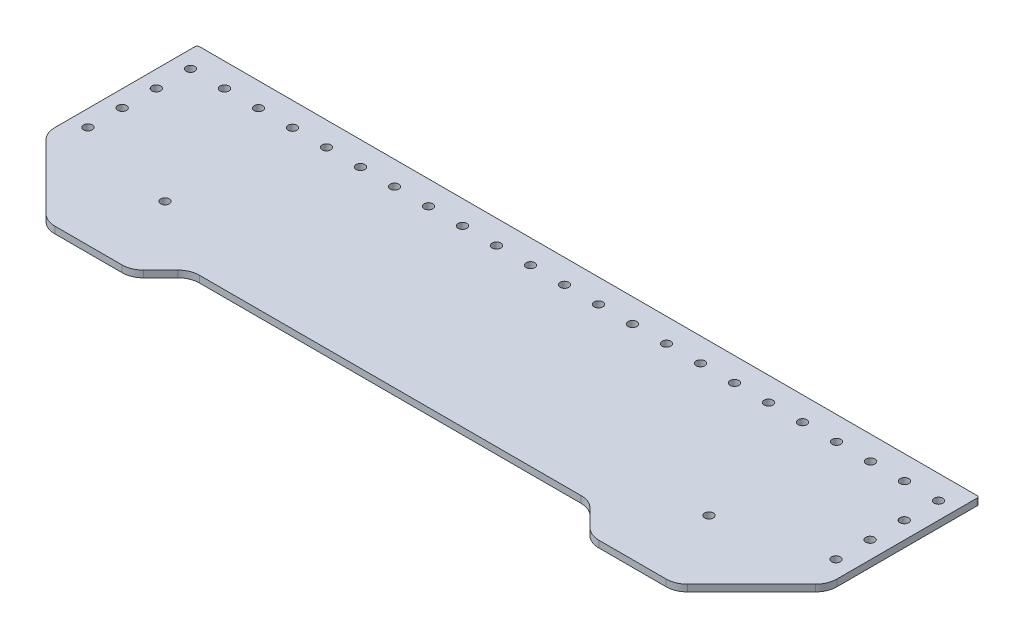
SolidWorks part; units mm, degrees
ref_plane "Front Plane" through (0, 0, 0) normal (0, 0, 1) x (1, 0, 0)
ref_plane "Top Plane" through (0, 0, 0) normal (0, 1, 0) x (1, 0, 0)
ref_plane "Right Plane" through (0, 0, 0) normal (1, 0, 0) x (0, 0, -1)
sketch "Sketch3" plane through (0, 0, 0) normal (0, 1, 0) x (1, 0, 0)
  line L0 (0, 0) -> (50000, 0) construction
  line L1 (184, -59.5875) -> (-184, -59.5875) construction
  line L2 (184, -59.5875) -> (184, 59.5875) construction
  line L3 (184, 59.5875) -> (-184, 59.5875) construction
  line L4 (-184, -59.5875) -> (-184, 59.5875) construction
  line L5 (184, -59.5875) -> (-184, 59.5875) construction
  line L6 (184, 59.5875) -> (-184, -59.5875) construction
  line L7 (0, 0) -> (0, -50000) construction
  line L8 (-141.9903, -11.5875) -> (49858.0097, -11.5875) construction
  line L9 (-130.2701, 7.3771) -> (-33.4655, 18.9646) construction
  line L10 (-128, -11.5875) -> (-31.1955, 0) construction
  line L11 (-125.7299, -30.5521) -> (-28.9254, -18.9646) construction
  line L12 (-49.1677, -33.5875) -> (49950.8323, -33.5875) construction
  line L13 (-47.419, -47.5875) -> (-50047.419, -47.5875) construction
  line L14 (-184, -11.5875) -> (-148, -47.5875)
  line L15 (-128, -11.5875) -> (-128, -50011.5875) construction
  line L16 (-148, -47.5875) -> (-108, -47.5875)
  line L17 (-94, -33.5875) -> (-108, -47.5875)
  line L18 (-94, -33.5875) -> (94, -33.5875)
  line L19 (-184, -11.5875) -> (-184, 59.5875)
  line L20 (-184, 59.5875) -> (184, 59.5875)
  line L21 (184, -11.5875) -> (184, 59.5875)
  line L22 (184, -11.5875) -> (148, -47.5875)
  line L23 (148, -47.5875) -> (108, -47.5875)
  line L24 (94, -33.5875) -> (108, -47.5875)
  line L26 (-15.1955, -16) -> (-47.1955, -16) construction
  line L27 (-15.1955, -16) -> (-15.1955, 16) construction
  line L28 (-15.1955, 16) -> (-47.1955, 16) construction
  line L29 (-47.1955, -16) -> (-47.1955, 16) construction
  line L30 (-15.1955, -16) -> (-47.1955, 16) construction
  line L31 (-15.1955, 16) -> (-47.1955, -16) construction
  line L32 (-9.1955, -22) -> (-53.1955, -22) construction
  line L33 (-9.1955, -22) -> (-9.1955, 22) construction
  line L34 (-9.1955, 22) -> (-53.1955, 22) construction
  line L35 (-53.1955, -22) -> (-53.1955, 22) construction
  line L36 (-9.1955, -22) -> (-53.1955, 22) construction
  line L37 (-9.1955, 22) -> (-53.1955, -22) construction
  circle A0 centre (-128, -11.5875) radius 48 construction
  circle A1 centre (-128, -11.5875) radius 19.1 construction
  circle A2 centre (-31.1955, 0) radius 19.1 construction
  arc A3 (-33.4655, 18.9646) -> (-28.9254, -18.9646) centre (-31.1955, 0) cw construction
  arc A4 (-130.2701, 7.3771) -> (-125.7299, -30.5521) centre (-128, -11.5875) ccw construction
  circle A5 centre (-128, -11.5875) radius 2.05
  circle A7 centre (128, -11.5875) radius 2.05
  circle A9 centre (-53.1955, 22) radius 2.05 construction
  circle A10 centre (-53.1955, -22) radius 2.05 construction
  circle A11 centre (53.1955, 22) radius 2.05 construction
  circle A12 centre (53.1955, -22) radius 2.05 construction
  circle A13 centre (-31.1955, 0) radius 17.5 construction
  circle A14 centre (31.1955, 0) radius 17.5 construction
  point P0 (0, 0)
  point P36 (0, 59.5875)
  point P40 (0, -33.5875)
  dimension "D4" = 96
  dimension "D6" = 38.2
  dimension "D12" = 4.1
  dimension "D15" = 35
  dimension "D1" = 368
  dimension "D2" = 119.175
  dimension "D3" = 48
  dimension "D5" = 56
  dimension "D8" = 26
  dimension "D9" = 12
  dimension "D10" = 45
  dimension "D11" = 45
  dimension "D13" = 32
  dimension "D14" = 44
extrude "Boss-Extrude2" add sketch "Sketch3" along normal blind 3.175
fillet "Fillet1" radius 10 8 edges at (184, 1.5875, 11.5875) (148, 1.5875, 47.5875) (108, 1.5875, 47.5875) (94, 1.5875, 33.5875) (-94, 1.5875, 33.5875) (-108, 1.5875, 47.5875) (-148, 1.5875, 47.5875) (-184, 1.5875, 11.5875)
fillet "Fillet2" radius 1 2 edges at (184, 1.5875, -59.5875) (-184, 1.5875, -59.5875)
sketch "Sketch5" plane through (0, 3.175, 0) normal (0, 1, 0) x (1, 0, 0)
  line L0 (0, 0) -> (0, -50000) construction
  circle A0 centre (-128, -11.5875) radius 48
  circle A1 centre (128, -11.5875) radius 48
  dimension "D1" = 96
sketch "Sketch6" plane through (0, 3.175, 0) normal (0, 1, 0) x (1, 0, 0)
  line L0 (0, 0) -> (0, -50000) construction
  line L1 (-160.014, 32.4127) -> (49839.986, 32.4127) construction
  line L2 (0, 0) -> (50000, 0) construction
  line L3 (21.2444, 56.4125) -> (50021.2444, 56.4125) construction
  line L4 (21.9898, 48.4125) -> (50021.9898, 48.4125) construction
  line L5 (183, 59.5875) -> (-183, 59.5875) construction
  line L6 (-176, 42.191) -> (-176, -49957.809) construction
  line L7 (-184, 58.5875) -> (-184, -7.4454) construction
  line L8 (-176, 48.4125) -> (-160, 48.4125) construction
  line L9 (-176, 48.4125) -> (-176.0869, 32.4127) construction
  circle A0 centre (-176, 48.4125) radius 2.05
  circle A1 centre (-160, 48.4125) radius 2.05
  circle A2 centre (-144, 48.4125) radius 2.05
  circle A3 centre (-128, 48.4125) radius 2.05
  circle A4 centre (-112, 48.4125) radius 2.05
  circle A5 centre (-96, 48.4125) radius 2.05
  circle A6 centre (-80, 48.4125) radius 2.05
  circle A7 centre (-64, 48.4125) radius 2.05
  circle A8 centre (-48, 48.4125) radius 2.05
  circle A9 centre (-32, 48.4125) radius 2.05
  circle A10 centre (-16, 48.4125) radius 2.05
  circle A11 centre (0, 48.4125) radius 2.05
  circle A12 centre (16, 48.4125) radius 2.05
  circle A13 centre (32, 48.4125) radius 2.05
  circle A14 centre (48, 48.4125) radius 2.05
  circle A15 centre (64, 48.4125) radius 2.05
  circle A16 centre (80, 48.4125) radius 2.05
  circle A17 centre (96, 48.4125) radius 2.05
  circle A18 centre (112, 48.4125) radius 2.05
  circle A19 centre (128, 48.4125) radius 2.05
  circle A20 centre (144, 48.4125) radius 2.05
  circle A21 centre (160, 48.4125) radius 2.05
  circle A22 centre (176, 48.4125) radius 2.05
  circle A23 centre (-160.0869, 32.4127) radius 2.05 construction
  circle A24 centre (-144.0869, 32.4127) radius 2.05 construction
  circle A25 centre (-128.0869, 32.4127) radius 2.05 construction
  circle A26 centre (-112.0869, 32.4127) radius 2.05 construction
  circle A27 centre (-96.0869, 32.4127) radius 2.05 construction
  circle A28 centre (-80.0869, 32.4127) radius 2.05 construction
  circle A29 centre (-64.0869, 32.4127) radius 2.05 construction
  circle A30 centre (-48.0869, 32.4127) radius 2.05 construction
  circle A31 centre (-32.0869, 32.4127) radius 2.05 construction
  circle A32 centre (-16.0869, 32.4127) radius 2.05 construction
  circle A33 centre (-0.0869, 32.4127) radius 2.05 construction
  circle A34 centre (15.9131, 32.4127) radius 2.05 construction
  circle A35 centre (31.9131, 32.4127) radius 2.05 construction
  circle A36 centre (47.9131, 32.4127) radius 2.05 construction
  circle A37 centre (63.9131, 32.4127) radius 2.05 construction
  circle A38 centre (79.9131, 32.4127) radius 2.05 construction
  circle A39 centre (95.9131, 32.4127) radius 2.05 construction
  circle A40 centre (111.9131, 32.4127) radius 2.05 construction
  circle A41 centre (127.9131, 32.4127) radius 2.05 construction
  circle A42 centre (143.9131, 32.4127) radius 2.05 construction
  circle A43 centre (159.9131, 32.4127) radius 2.05 construction
  circle A44 centre (175.9131, 32.4127) radius 2.05
  circle A45 centre (-160.1738, 16.413) radius 2.05 construction
  circle A46 centre (-144.1738, 16.413) radius 2.05 construction
  circle A47 centre (-128.1738, 16.413) radius 2.05 construction
  circle A48 centre (-112.1738, 16.413) radius 2.05 construction
  circle A49 centre (-96.1738, 16.413) radius 2.05 construction
  circle A50 centre (-80.1738, 16.413) radius 2.05 construction
  circle A51 centre (-64.1738, 16.413) radius 2.05 construction
  circle A52 centre (-48.1738, 16.413) radius 2.05 construction
  circle A53 centre (-32.1738, 16.413) radius 2.05 construction
  circle A54 centre (-16.1738, 16.413) radius 2.05 construction
  circle A55 centre (-0.1738, 16.413) radius 2.05 construction
  circle A56 centre (15.8262, 16.413) radius 2.05 construction
  circle A57 centre (31.8262, 16.413) radius 2.05 construction
  circle A58 centre (47.8262, 16.413) radius 2.05 construction
  circle A59 centre (63.8262, 16.413) radius 2.05 construction
  circle A60 centre (79.8262, 16.413) radius 2.05 construction
  circle A61 centre (95.8262, 16.413) radius 2.05 construction
  circle A62 centre (111.8262, 16.413) radius 2.05 construction
  circle A63 centre (127.8262, 16.413) radius 2.05 construction
  circle A64 centre (143.8262, 16.413) radius 2.05 construction
  circle A65 centre (159.8262, 16.413) radius 2.05 construction
  circle A66 centre (175.8262, 16.413) radius 2.05
  circle A67 centre (-160.2607, 0.4132) radius 2.05 construction
  circle A68 centre (-144.2607, 0.4132) radius 2.05 construction
  circle A69 centre (-128.2607, 0.4132) radius 2.05 construction
  circle A70 centre (-112.2607, 0.4132) radius 2.05 construction
  circle A71 centre (-96.2607, 0.4132) radius 2.05 construction
  circle A72 centre (-80.2607, 0.4132) radius 2.05 construction
  circle A73 centre (-64.2607, 0.4132) radius 2.05 construction
  circle A74 centre (-48.2607, 0.4132) radius 2.05 construction
  circle A75 centre (-32.2607, 0.4132) radius 2.05 construction
  circle A76 centre (-16.2607, 0.4132) radius 2.05 construction
  circle A77 centre (-0.2607, 0.4132) radius 2.05 construction
  circle A78 centre (15.7393, 0.4132) radius 2.05 construction
  circle A79 centre (31.7393, 0.4132) radius 2.05 construction
  circle A80 centre (47.7393, 0.4132) radius 2.05 construction
  circle A81 centre (63.7393, 0.4132) radius 2.05 construction
  circle A82 centre (79.7393, 0.4132) radius 2.05 construction
  circle A83 centre (95.7393, 0.4132) radius 2.05 construction
  circle A84 centre (111.7393, 0.4132) radius 2.05 construction
  circle A85 centre (127.7393, 0.4132) radius 2.05 construction
  circle A86 centre (143.7393, 0.4132) radius 2.05 construction
  circle A87 centre (159.7393, 0.4132) radius 2.05 construction
  circle A88 centre (175.7393, 0.4132) radius 2.05
  circle A89 centre (-160.3476, -15.5866) radius 2.05 construction
  circle A90 centre (-144.3476, -15.5866) radius 2.05 construction
  circle A91 centre (-128.3476, -15.5866) radius 2.05 construction
  circle A92 centre (-112.3476, -15.5866) radius 2.05 construction
  circle A93 centre (-96.3476, -15.5866) radius 2.05 construction
  circle A94 centre (-80.3476, -15.5866) radius 2.05 construction
  circle A95 centre (-64.3476, -15.5866) radius 2.05 construction
  circle A96 centre (-48.3476, -15.5866) radius 2.05 construction
  circle A97 centre (-32.3476, -15.5866) radius 2.05 construction
  circle A98 centre (-16.3476, -15.5866) radius 2.05 construction
  circle A99 centre (-0.3476, -15.5866) radius 2.05 construction
  circle A100 centre (15.6524, -15.5866) radius 2.05 construction
  circle A101 centre (31.6524, -15.5866) radius 2.05 construction
  circle A102 centre (47.6524, -15.5866) radius 2.05 construction
  circle A103 centre (63.6524, -15.5866) radius 2.05 construction
  circle A104 centre (79.6524, -15.5866) radius 2.05 construction
  circle A105 centre (95.6524, -15.5866) radius 2.05 construction
  circle A106 centre (111.6524, -15.5866) radius 2.05 construction
  circle A107 centre (127.6524, -15.5866) radius 2.05 construction
  circle A108 centre (143.6524, -15.5866) radius 2.05 construction
  circle A109 centre (159.6524, -15.5866) radius 2.05 construction
  circle A110 centre (175.6524, -15.5866) radius 2.05 construction
  circle A111 centre (-160.4345, -31.5863) radius 2.05 construction
  circle A112 centre (-144.4345, -31.5863) radius 2.05 construction
  circle A113 centre (-128.4345, -31.5863) radius 2.05 construction
  circle A114 centre (-112.4345, -31.5863) radius 2.05 construction
  circle A115 centre (-96.4345, -31.5863) radius 2.05 construction
  circle A116 centre (-80.4345, -31.5863) radius 2.05 construction
  circle A117 centre (-64.4345, -31.5863) radius 2.05 construction
  circle A118 centre (-48.4345, -31.5863) radius 2.05 construction
  circle A119 centre (-32.4345, -31.5863) radius 2.05 construction
  circle A120 centre (-16.4345, -31.5863) radius 2.05 construction
  circle A121 centre (-0.4345, -31.5863) radius 2.05 construction
  circle A122 centre (15.5655, -31.5863) radius 2.05 construction
  circle A123 centre (31.5655, -31.5863) radius 2.05 construction
  circle A124 centre (47.5655, -31.5863) radius 2.05 construction
  circle A125 centre (63.5655, -31.5863) radius 2.05 construction
  circle A126 centre (79.5655, -31.5863) radius 2.05 construction
  circle A127 centre (95.5655, -31.5863) radius 2.05 construction
  circle A128 centre (111.5655, -31.5863) radius 2.05 construction
  circle A129 centre (127.5655, -31.5863) radius 2.05 construction
  circle A130 centre (143.5655, -31.5863) radius 2.05 construction
  circle A131 centre (159.5655, -31.5863) radius 2.05 construction
  circle A132 centre (175.5655, -31.5863) radius 2.05 construction
  circle A133 centre (-160.5214, -47.5861) radius 2.05 construction
  circle A134 centre (-144.5214, -47.5861) radius 2.05 construction
  circle A135 centre (-128.5214, -47.5861) radius 2.05 construction
  circle A136 centre (-112.5214, -47.5861) radius 2.05 construction
  circle A137 centre (-96.5214, -47.5861) radius 2.05 construction
  circle A138 centre (-80.5214, -47.5861) radius 2.05 construction
  circle A139 centre (-64.5214, -47.5861) radius 2.05 construction
  circle A140 centre (-48.5214, -47.5861) radius 2.05 construction
  circle A141 centre (-32.5214, -47.5861) radius 2.05 construction
  circle A142 centre (-16.5214, -47.5861) radius 2.05 construction
  circle A143 centre (-0.5214, -47.5861) radius 2.05 construction
  circle A144 centre (15.4786, -47.5861) radius 2.05 construction
  circle A145 centre (31.4786, -47.5861) radius 2.05 construction
  circle A146 centre (47.4786, -47.5861) radius 2.05 construction
  circle A147 centre (63.4786, -47.5861) radius 2.05 construction
  circle A148 centre (79.4786, -47.5861) radius 2.05 construction
  circle A149 centre (95.4786, -47.5861) radius 2.05 construction
  circle A150 centre (111.4786, -47.5861) radius 2.05 construction
  circle A151 centre (127.4786, -47.5861) radius 2.05 construction
  circle A152 centre (143.4786, -47.5861) radius 2.05 construction
  circle A153 centre (159.4786, -47.5861) radius 2.05 construction
  circle A154 centre (175.4786, -47.5861) radius 2.05 construction
  circle A155 centre (-176.0869, 32.4127) radius 2.05
  circle A156 centre (-176.1738, 16.413) radius 2.05
  circle A157 centre (-176.2607, 0.4132) radius 2.05
  circle A158 centre (-176.3476, -15.5866) radius 2.05 construction
  circle A159 centre (-176.4345, -31.5863) radius 2.05 construction
  circle A160 centre (-176.5214, -47.5861) radius 2.05 construction
  circle A161 centre (-25.0869, 32.4127) radius 2.05 construction
  circle A162 centre (25.0869, 32.4127) radius 2.05 construction
  circle A163 centre (109.9131, 32.4127) radius 2.05 construction
  circle A164 centre (-109.9131, 32.4127) radius 2.05 construction
  dimension "D4" = 4.1
  dimension "D1" = 8
  dimension "D2" = 3.175
  dimension "D3" = 8
  dimension "D7" = 16
  dimension "D8" = 16
  dimension "D9" = 23.9131
  dimension "D10" = 135
  dimension "D11" = 270
  dimension "D5" = 23
  dimension "D6" = 7
extrude "Cut-Extrude3" cut sketch "Sketch6" against normal blind 3.18
equation "\"wheelDiameter\"= 96mm"
equation "\"thick\"= 3.175mm"
equation "\"sh\"= 4.1mm"
equation "\"w\"= 368mm"
equation "\"h\"= \"wheelDiameter\" + 20mm + 3.175mm"
equation "\"pitchDiameter\"= 38.2mm"
equation "\"D1@Sketch3\"=\"w\""
equation "\"D2@Sketch3\"=\"h\""
equation "\"D3@Sketch3\"=\"wheelDiameter\"/2"
equation "\"D4@Sketch3\"=\"wheelDiameter\""
equation "\"D5@Sketch3\"=\"wheelDiameter\"/2 +8"
equation "\"D6@Sketch3\"=\"pitchDiameter\""
equation "\"beltPitch\"= 315mm"
equation "\"D7@Sketch3\"=\"beltPitch\""
equation "\"D12@Sketch3\"=\"sh\""
equation "\"D1@Boss-Extrude2\"=\"thick\""
equation "\"D1@Sketch5\"=\"wheelDiameter\""
equation "\"D2@Sketch6\"=\"thick\""
equation "\"D4@Sketch6\"=\"sh\""
